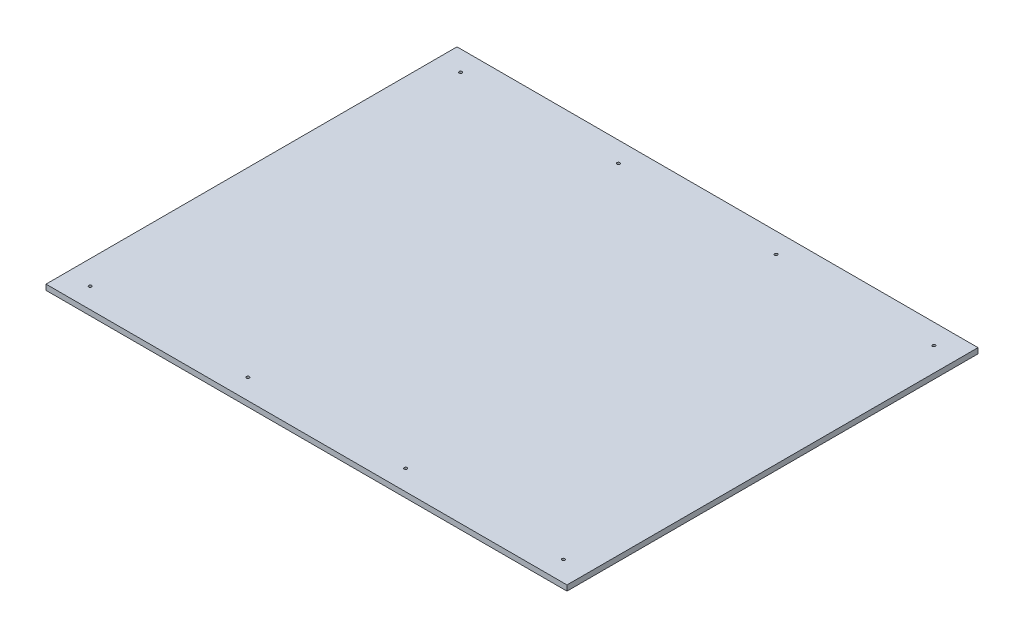
SolidWorks part; units mm, degrees
ref_plane "Front" through (0, 0, 0) normal (0, 0, 1) x (1, 0, 0)
ref_plane "Top" through (0, 0, 0) normal (0, 1, 0) x (1, 0, 0)
ref_plane "Right" through (0, 0, 0) normal (1, 0, 0) x (0, 0, -1)
sketch "Sketch1" plane through (0, 0, 0) normal (0, 1, 0) x (1, 0, 0)
  line L1 (-571.5, 450.85) -> (571.5, 450.85)
  line L2 (-571.5, 450.85) -> (-571.5, -450.85)
  line L3 (-571.5, -450.85) -> (571.5, -450.85)
  line L4 (571.5, 450.85) -> (571.5, -450.85)
  line L5 (-571.5, 450.85) -> (571.5, -450.85) construction
  line L6 (-571.5, -450.85) -> (571.5, 450.85) construction
  point P0 (0, 0)
  dimension "D1" = 901.7
  dimension "D2" = 1143
extrude "Boss-Extrude1" add sketch "Sketch1" along normal blind 11.9062
hole_wizard "1/4 (0.25) Diameter Hole1" positions "Sketch2" profile "Sketch3" hole size "1/4" standard "ANSI Inch" end condition through all
sketch "Sketch2" plane through (0, 0, 0) normal (0, -1, 0) x (-1, 0, 0)
  line L0 (571.5, 450.85) -> (571.5, -450.85) construction
  line L1 (571.5, -450.85) -> (-571.5, -450.85) construction
  line L2 (519.1125, -406.4) -> (173.0375, -406.4) construction
  line L3 (519.1125, -406.4) -> (519.1125, 406.4) construction
  point P0 (519.1125, -406.4)
  point P41 (173.0375, -406.4)
  point P42 (-173.0375, -406.4)
  point P43 (-519.1125, -406.4)
  point P44 (173.0375, 406.4)
  point P45 (-173.0375, 406.4)
  point P46 (-519.1125, 406.4)
  point P47 (519.1125, 406.4)
  dimension "D1" = 52.3875
  dimension "D2" = 44.45
  dimension "D5" = 346.075
  dimension "D6" = 812.8
  dimension "D3" = 4
  dimension "D4" = 2
sketch "Sketch3" plane through (-519.1125, 0, 406.4) normal (1, 0, 0) x (0, 0, -1)
  line L0 (0, 0) -> (0, 11.9062)
  line L1 (0, 11.9062) -> (3.175, 11.9062)
  line L2 (3.175, 11.9062) -> (3.175, 0)
  line L5 (3.175, 0) -> (0, 0)
  line L11 (0, -6.35) -> (0, 107.95) construction
  dimension "Thru Hole Dia." = 6.35
  dimension "Thru Hole Depth" = 11.9062
